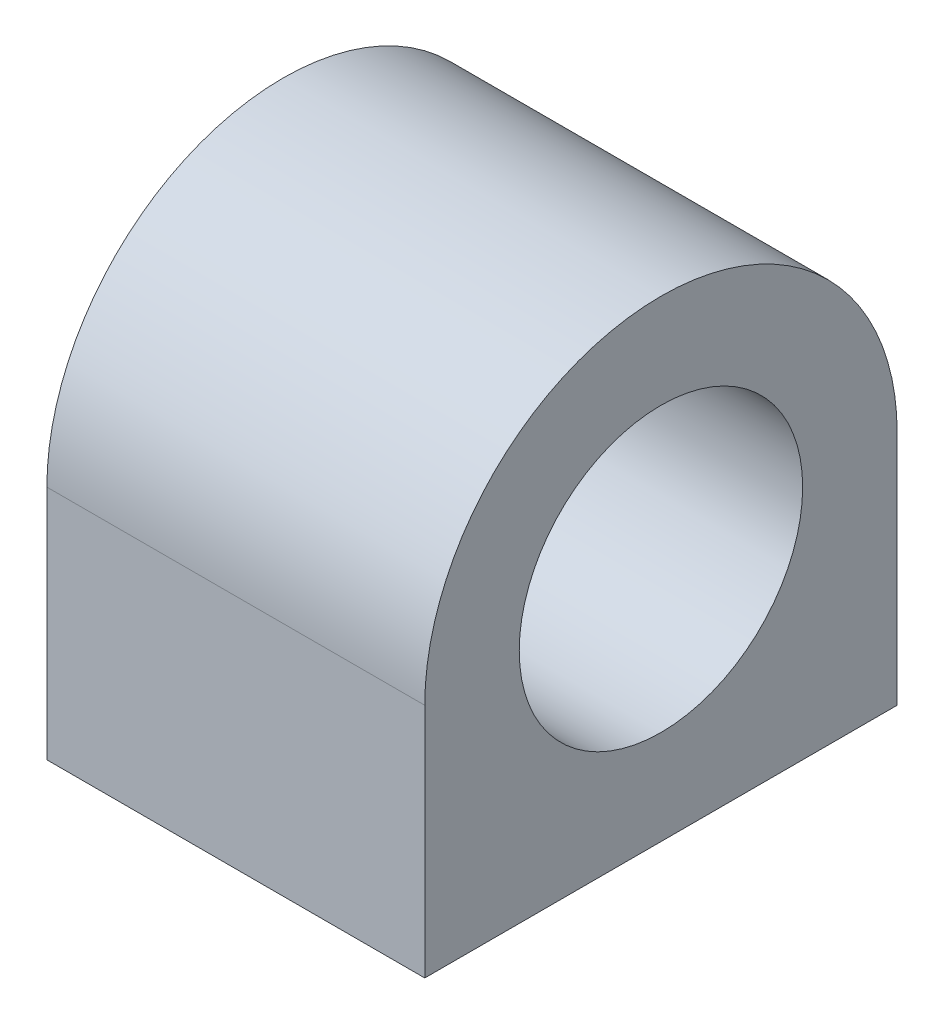
SolidWorks part; units mm, degrees
ref_plane "Plan de face" through (0, 0, 0) normal (0, 0, 1) x (1, 0, 0)
ref_plane "Plan de dessus" through (0, 0, 0) normal (0, 1, 0) x (1, 0, 0)
ref_plane "Plan de droite" through (0, 0, 0) normal (1, 0, 0) x (0, 0, -1)
sketch "Esquisse3" plane through (0, 0, 0) normal (1, 0, 0) x (0, 0, -1)
  line L1 (0, 0) -> (25, 0)
  line L2 (0, 0) -> (0, 12.5)
  line L3 (0, 12.5) -> (25, 12.5)
  line L4 (25, 0) -> (25, 12.5)
  circle A0 centre (12.5, 12.5) radius 12.5
  dimension "D1" = 25
  dimension "D3" = 25
  dimension "D2" = 12.5
extrude "Boss.-Extru.2" add sketch "Esquisse3" along normal blind 20 contours L3 A0 | L3 A0 | A0 L2 L1 L4
sketch "Esquisse4" plane through (0, 0, 0) normal (-1, 0, 0) x (0, 0, 1)
  line L0 (0, 0) -> (0, 12.5) construction
  line L1 (0, 0) -> (-25, 0) construction
  circle A0 centre (-12.5, 12.5) radius 7.5
  dimension "D1" = 15
  dimension "D2" = 12.5
  dimension "D3" = 12.5
extrude "Enlèv. mat.-Extru.1" cut sketch "Esquisse4" against normal through all
sketch "Esquisse7" plane through (0, 0, 0) normal (0, -1, 0) x (1, 0, 0)
  line L0 (0, 0) -> (0, -25) construction
  line L1 (20, -25) -> (0, -25) construction
  line L2 (20, 0) -> (0, 0) construction
  point P0 (10, -20)
  point P1 (10, -5)
  dimension "D1" = 10
  dimension "D2" = 10
  dimension "D3" = 5
  dimension "D4" = 5
hole_wizard "Trou taraudé M51" positions "Esquisse3D2" profile "Esquisse8" tap size "M5" standard "ISO"
sketch3d "Esquisse3D2"
  point P0 (10, 0, -5)
  point P3 (10, 0, -20)
cosmetic thread "Filetage de perçage1" parameters "D1"=10, "D2"=5
cosmetic thread "Filetage de perçage2" parameters "D1"=10, "D2"=5
sketch "Esquisse8" plane through (10, 0, -5) normal (1, 0, 0) x (0, 0, -1)
  line L0 (0, 0) -> (0, 6.2618)
  line L1 (0, 6.2618) -> (2.1, 5)
  line L2 (2.1, 5) -> (2.1, 0)
  line L5 (2.1, 0) -> (0, 0)
  line L10 (0, 6.2618) -> (-2.1, 5) construction
  line L11 (0, -6.35) -> (0, 107.95) construction
  dimension "Diamètre du trou pour taraudage" = 4.2
  dimension "Profondeur du trou pour taraudage" = 5
  dimension "Angle de pointe" = 118
equation "\"D2@Esquisse7\"=\"D1@Esquisse7\""
